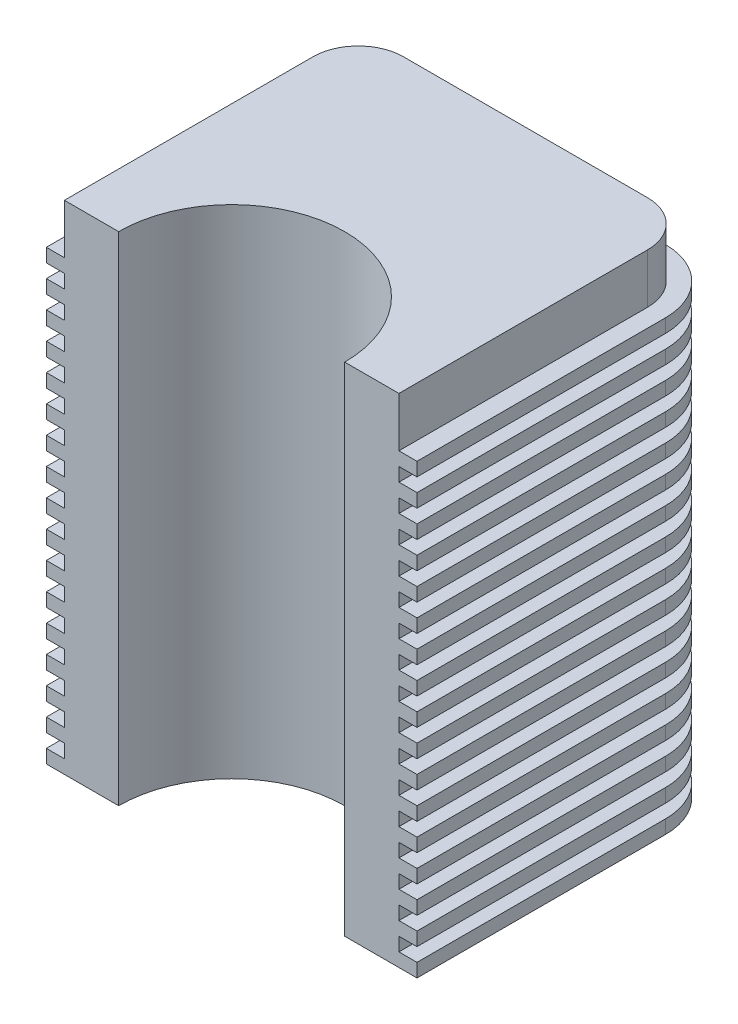
SolidWorks part; units mm, degrees
ref_plane "Front Plane" through (0, 0, 0) normal (0, 0, 1) x (1, 0, 0)
ref_plane "Top Plane" through (0, 0, 0) normal (0, 1, 0) x (1, 0, 0)
ref_plane "Right Plane" through (0, 0, 0) normal (1, 0, 0) x (0, 0, -1)
sketch "Sketch1" plane through (0, 0, 0) normal (0, 1, 0) x (1, 0, 0)
  line L0 (25, 0) -> (37, 0)
  line L1 (37, 0) -> (37, 55)
  line L2 (27, 65) -> (-27, 65)
  line L3 (0, 0) -> (0, 48.4991) construction
  line L4 (-25, 0) -> (-37, 0)
  line L5 (-37, 0) -> (-37, 55)
  arc A0 (25, 0) -> (-25, 0) centre (0, 0) ccw
  arc A1 (37, 55) -> (27, 65) centre (27, 55) ccw
  arc A2 (-37, 55) -> (-27, 65) centre (-27, 55) cw
  point P11 (0, 65)
  point P13 (37, 65)
  point P16 (-37, 65)
  dimension "D1" = 50
  dimension "D4" = 10
  dimension "D2" = 12
  dimension "D3" = 65
extrude "Boss-Extrude1" add sketch "Sketch1" along normal blind 110
sketch "Sketch2" plane through (0, 0, 0) normal (0, -1, 0) x (1, 0, 0)
  line L1 (41, -55) -> (41, 0)
  line L2 (-27, -69) -> (27, -69)
  line L3 (-41, 0) -> (-41, -55)
  line L5 (-25, 0) -> (-37, 0)
  line L6 (-37, 0) -> (-37, -55)
  line L7 (-27, -65) -> (27, -65)
  line L8 (37, -55) -> (37, 0)
  line L9 (37, 0) -> (25, 0)
  line L10 (-25, 0) -> (-37, 0)
  line L11 (-37, 0) -> (-37, -55)
  line L12 (-27, -65) -> (27, -65)
  line L13 (37, -55) -> (37, 0)
  line L14 (37, 0) -> (25, 0)
  line L15 (-37, 0) -> (-41, 0)
  line L16 (37, 0) -> (41, 0)
  line L17 (-41, 4) -> (-41, -55) construction
  line L18 (-20.6155, 4) -> (-41, 4) construction
  line L19 (41, 4) -> (20.6155, 4) construction
  line L20 (41, -55) -> (41, 4) construction
  arc A1 (27, -69) -> (41, -55) centre (27, -55) ccw
  arc A2 (-41, -55) -> (-27, -69) centre (-27, -55) ccw
  arc A3 (-25, 0) -> (25, 0) centre (0, 0) ccw
  arc A4 (-37, -55) -> (-27, -65) centre (-27, -55) ccw
  arc A5 (27, -65) -> (37, -55) centre (27, -55) ccw
  arc A6 (-25, 0) -> (25, 0) centre (0, 0) ccw
  arc A7 (-37, -55) -> (-27, -65) centre (-27, -55) ccw
  arc A8 (27, -65) -> (37, -55) centre (27, -55) ccw
  arc A9 (-20.6155, 4) -> (20.6155, 4) centre (0, 0) ccw construction
  line M19 (-37, 0) -> (-37, -55)
  arc M20 (-37, -55) -> (-27, -65) centre (-27, -55) ccw
  line M21 (-27, -65) -> (27, -65)
  arc M22 (27, -65) -> (37, -55) centre (27, -55) ccw
  line M23 (37, -55) -> (37, 0)
  dimension "D1" = 0
  dimension "D2" = 4
extrude "Boss-Extrude2" add sketch "Sketch2" against normal blind 3 contours L3 A2 L2 A1 L1 L16 L15 M23 M22 M21 M20 M19
pattern_linear "LPattern1" count 17 spacing 6 along (0, 1, 0) of "Boss-Extrude2"
